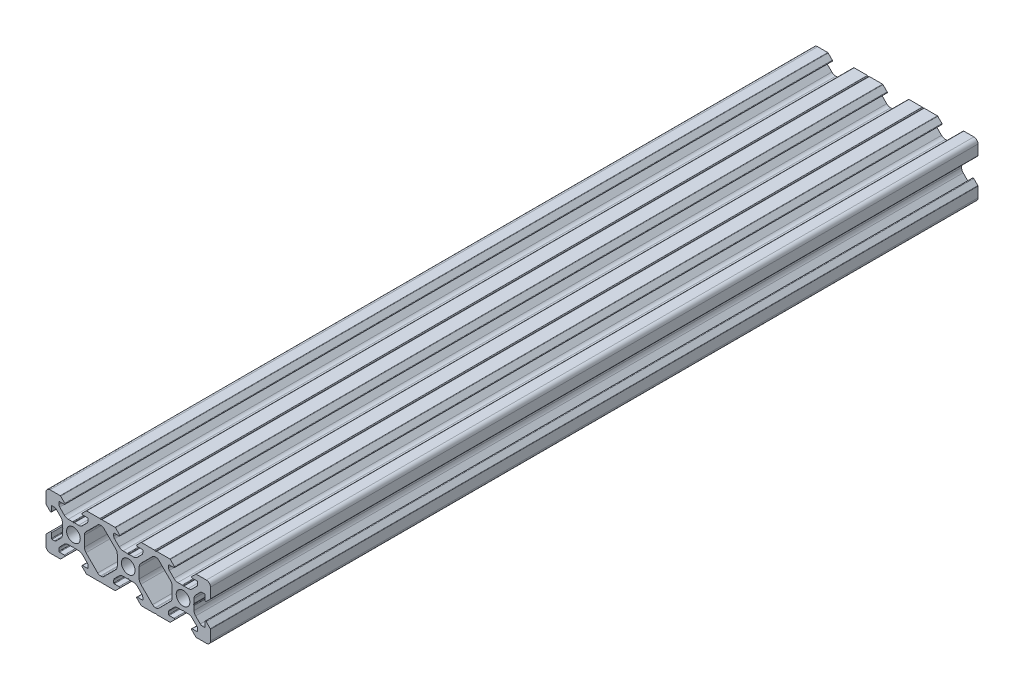
SolidWorks part; units mm, degrees
material "6061 Сплав"
ref_plane "Спереди" through (0, 0, 0) normal (0, 0, 1) x (1, 0, 0)
ref_plane "Сверху" through (0, 0, 0) normal (0, 1, 0) x (1, 0, 0)
ref_plane "Справа" through (0, 0, 0) normal (1, 0, 0) x (0, 0, -1)
sketch "Сечение" plane through (0, 0, 0) normal (0, 0, 1) x (1, 0, 0)
  line L84 (77.3691, 77.5727) -> (77.3691, 81.3703)
  line L85 (76.7833, 82.7845) -> (72.5063, 87.0614)
  line L86 (71.5164, 87.4715) -> (71.2217, 87.4715)
  line L87 (65.9548, 82.7845) -> (70.2318, 87.0614)
  line L88 (65.3691, 77.5727) -> (65.3691, 81.3703)
  line L89 (65.9548, 76.1585) -> (70.2318, 71.8815)
  line L90 (71.5164, 71.4715) -> (71.2217, 71.4715)
  line L91 (76.7833, 76.1585) -> (72.5063, 71.8815)
  line L92 (45.9548, 76.1585) -> (50.2318, 71.8815)
  line L93 (51.2217, 71.4715) -> (51.5164, 71.4715)
  line L94 (56.7833, 76.1585) -> (52.5063, 71.8815)
  line L95 (57.3691, 77.5727) -> (57.3691, 81.3703)
  line L96 (56.7833, 82.7845) -> (52.5063, 87.0614)
  line L97 (51.2217, 87.4715) -> (51.5164, 87.4715)
  line L98 (45.9548, 82.7845) -> (50.2318, 87.0614)
  line L99 (45.3691, 77.5727) -> (45.3691, 81.3703)
  line L100 (37.3691, 79.8092) -> (37.3691, 81.3703)
  line L101 (36.7833, 82.7845) -> (35.0892, 84.4786)
  line L102 (34.382, 84.7715) -> (33.5691, 84.7715)
  line L103 (33.3691, 84.5715) -> (33.3691, 82.8015)
  line L104 (31.4423, 84.1247) -> (32.9423, 82.6247)
  line L105 (31.3691, 84.3015) -> (31.3691, 87.9715)
  line L106 (36.7158, 89.3983) -> (38.2158, 87.8983)
  line L107 (41.1875, 83.4167) -> (41.3691, 83.2715)
  line L108 (41.5506, 83.4167) -> (41.3691, 83.2715)
  line L109 (43.2678, 83.4715) -> (41.7067, 83.4715)
  line L110 (46.3762, 85.7514) -> (44.682, 84.0573)
  line L111 (46.6691, 87.2715) -> (46.6691, 86.4585)
  line L112 (44.6991, 87.4715) -> (46.4691, 87.4715)
  line L113 (46.0223, 89.3983) -> (44.5223, 87.8983)
  line L114 (50.9934, 89.4715) -> (46.1991, 89.4715)
  line L115 (51.3691, 89.2715) -> (51.132, 89.4295)
  line L116 (51.3691, 89.2715) -> (51.6061, 89.4295)
  line L117 (51.7447, 89.4715) -> (56.5391, 89.4715)
  line L118 (56.7158, 89.3983) -> (58.2158, 87.8983)
  line L119 (58.0391, 87.4715) -> (56.2691, 87.4715)
  line L120 (56.0691, 87.2715) -> (56.0691, 86.4585)
  line L121 (56.3619, 85.7514) -> (58.0561, 84.0573)
  line L122 (59.4703, 83.4715) -> (61.0314, 83.4715)
  line L123 (61.1875, 83.4167) -> (61.3691, 83.2715)
  line L124 (61.5506, 83.4167) -> (61.3691, 83.2715)
  line L125 (63.2678, 83.4715) -> (61.7067, 83.4715)
  line L126 (66.3762, 85.7514) -> (64.682, 84.0573)
  line L127 (66.6691, 87.2715) -> (66.6691, 86.4585)
  line L128 (64.6991, 87.4715) -> (66.4691, 87.4715)
  line L129 (66.0223, 89.3983) -> (64.5223, 87.8983)
  line L130 (70.9934, 89.4715) -> (66.1991, 89.4715)
  line L131 (71.3691, 89.2715) -> (71.132, 89.4295)
  line L132 (71.3691, 89.2715) -> (71.6061, 89.4295)
  line L133 (71.7447, 89.4715) -> (76.5391, 89.4715)
  line L134 (76.7158, 89.3983) -> (78.2158, 87.8983)
  line L135 (78.0391, 87.4715) -> (76.2691, 87.4715)
  line L136 (76.0691, 87.2715) -> (76.0691, 86.4585)
  line L137 (76.3619, 85.7514) -> (78.0561, 84.0573)
  line L138 (79.4703, 83.4715) -> (81.0314, 83.4715)
  line L139 (81.1875, 83.4167) -> (81.3691, 83.2715)
  line L140 (81.5506, 83.4167) -> (81.3691, 83.2715)
  line L141 (84.682, 84.0573) -> (86.3762, 85.7514)
  line L142 (86.6691, 86.4585) -> (86.6691, 87.2715)
  line L143 (86.4691, 87.4715) -> (84.6991, 87.4715)
  line L144 (86.0223, 89.3983) -> (84.5223, 87.8983)
  line L145 (86.1991, 89.4715) -> (89.8691, 89.4715)
  line L146 (91.3691, 84.3015) -> (91.3691, 87.9715)
  line L147 (91.2958, 84.1247) -> (89.7958, 82.6247)
  line L148 (89.3691, 84.5715) -> (89.3691, 82.8015)
  line L149 (88.3561, 84.7715) -> (89.1691, 84.7715)
  line L150 (85.9548, 82.7845) -> (87.649, 84.4786)
  line L151 (85.3691, 79.8092) -> (85.3691, 81.3703)
  line L152 (85.3143, 79.653) -> (85.1691, 79.4715)
  line L153 (85.3143, 79.29) -> (85.1691, 79.4715)
  line L154 (85.3691, 79.1338) -> (85.3691, 77.5727)
  line L155 (85.9548, 76.1585) -> (87.649, 74.4644)
  line L156 (88.3561, 74.1715) -> (89.1691, 74.1715)
  line L157 (89.3691, 74.3715) -> (89.3691, 76.1415)
  line L158 (91.2958, 74.8183) -> (89.7958, 76.3183)
  line L159 (91.3691, 74.6415) -> (91.3691, 70.9715)
  line L160 (86.1991, 69.4715) -> (89.8691, 69.4715)
  line L161 (86.0223, 69.5447) -> (84.5223, 71.0447)
  line L162 (86.4691, 71.4715) -> (84.6991, 71.4715)
  line L163 (86.6691, 72.4845) -> (86.6691, 71.6715)
  line L164 (84.682, 74.8857) -> (86.3762, 73.1916)
  line L165 (81.7067, 75.4715) -> (83.2678, 75.4715)
  line L166 (81.5506, 75.5263) -> (81.3691, 75.6715)
  line L167 (81.1875, 75.5263) -> (81.3691, 75.6715)
  line L168 (79.4703, 75.4715) -> (81.0314, 75.4715)
  line L169 (76.3619, 73.1916) -> (78.0561, 74.8857)
  line L170 (76.0691, 71.6715) -> (76.0691, 72.4845)
  line L171 (78.0391, 71.4715) -> (76.2691, 71.4715)
  line L172 (76.7158, 69.5447) -> (78.2158, 71.0447)
  line L173 (71.7447, 69.4715) -> (76.5391, 69.4715)
  line L174 (71.3691, 69.6715) -> (71.6061, 69.5135)
  line L175 (71.3691, 69.6715) -> (71.132, 69.5135)
  line L176 (70.9934, 69.4715) -> (66.1991, 69.4715)
  line L177 (66.0223, 69.5447) -> (64.5223, 71.0447)
  line L178 (64.6991, 71.4715) -> (66.4691, 71.4715)
  line L179 (66.6691, 71.6715) -> (66.6691, 72.4845)
  line L180 (66.3762, 73.1916) -> (64.682, 74.8857)
  line L181 (63.2678, 75.4715) -> (61.7067, 75.4715)
  line L182 (61.5506, 75.5263) -> (61.3691, 75.6715)
  line L183 (61.1875, 75.5263) -> (61.3691, 75.6715)
  line L184 (59.4703, 75.4715) -> (61.0314, 75.4715)
  line L185 (56.3619, 73.1916) -> (58.0561, 74.8857)
  line L186 (56.0691, 71.6715) -> (56.0691, 72.4845)
  line L187 (58.0391, 71.4715) -> (56.2691, 71.4715)
  line L188 (56.7158, 69.5447) -> (58.2158, 71.0447)
  line L189 (51.7447, 69.4715) -> (56.5391, 69.4715)
  line L190 (51.3691, 69.6715) -> (51.6061, 69.5135)
  line L191 (51.3691, 69.6715) -> (51.132, 69.5135)
  line L192 (50.9934, 69.4715) -> (46.1991, 69.4715)
  line L193 (46.0223, 69.5447) -> (44.5223, 71.0447)
  line L194 (44.6991, 71.4715) -> (46.4691, 71.4715)
  line L195 (46.6691, 71.6715) -> (46.6691, 72.4845)
  line L196 (46.3762, 73.1916) -> (44.682, 74.8857)
  line L197 (43.2678, 75.4715) -> (41.7067, 75.4715)
  line L198 (41.5506, 75.5263) -> (41.3691, 75.6715)
  line L199 (41.1875, 75.5263) -> (41.3691, 75.6715)
  line L200 (41.0314, 75.4715) -> (39.4703, 75.4715)
  line L201 (38.0561, 74.8857) -> (36.3619, 73.1916)
  line L202 (36.0691, 72.4845) -> (36.0691, 71.6715)
  line L203 (36.2691, 71.4715) -> (38.0391, 71.4715)
  line L204 (36.7158, 69.5447) -> (38.2158, 71.0447)
  line L205 (36.5391, 69.4715) -> (32.8691, 69.4715)
  line L206 (31.3691, 74.6415) -> (31.3691, 70.9715)
  line L207 (31.4423, 74.8183) -> (32.9423, 76.3183)
  line L208 (33.3691, 74.3715) -> (33.3691, 76.1415)
  line L209 (34.382, 74.1715) -> (33.5691, 74.1715)
  line L210 (36.7833, 76.1585) -> (35.0892, 74.4644)
  line L211 (37.3691, 79.1338) -> (37.3691, 77.5727)
  line L212 (37.4238, 79.29) -> (37.5691, 79.4715)
  line L213 (37.4238, 79.653) -> (37.5691, 79.4715)
  line L214 (81.7067, 83.4715) -> (83.2678, 83.4715)
  line L215 (41.0314, 83.4715) -> (39.4703, 83.4715)
  line L216 (38.0561, 84.0573) -> (36.3619, 85.7514)
  line L217 (36.0691, 86.4585) -> (36.0691, 87.2715)
  line L218 (36.2691, 87.4715) -> (38.0391, 87.4715)
  line L219 (36.5391, 89.4715) -> (32.8691, 89.4715)
  circle A0 centre (81.3691, 79.4715) radius 2.5
  arc A1 (77.3691, 81.3703) -> (76.7833, 82.7845) centre (75.3691, 81.3703) ccw
  arc A2 (72.5063, 87.0614) -> (71.5164, 87.4715) centre (71.5164, 86.0715) ccw
  arc A3 (71.2217, 87.4715) -> (70.2318, 87.0614) centre (71.2217, 86.0715) ccw
  arc A4 (65.9548, 82.7845) -> (65.3691, 81.3703) centre (67.3691, 81.3703) ccw
  arc A5 (65.3691, 77.5727) -> (65.9548, 76.1585) centre (67.3691, 77.5727) ccw
  arc A6 (70.2318, 71.8815) -> (71.2217, 71.4715) centre (71.2217, 72.8715) ccw
  arc A7 (71.5164, 71.4715) -> (72.5063, 71.8815) centre (71.5164, 72.8715) ccw
  arc A8 (76.7833, 76.1585) -> (77.3691, 77.5727) centre (75.3691, 77.5727) ccw
  arc A9 (50.2318, 71.8815) -> (51.2217, 71.4715) centre (51.2217, 72.8715) ccw
  arc A10 (51.5164, 71.4715) -> (52.5063, 71.8815) centre (51.5164, 72.8715) ccw
  arc A11 (56.7833, 76.1585) -> (57.3691, 77.5727) centre (55.3691, 77.5727) ccw
  arc A12 (57.3691, 81.3703) -> (56.7833, 82.7845) centre (55.3691, 81.3703) ccw
  arc A13 (52.5063, 87.0614) -> (51.5164, 87.4715) centre (51.5164, 86.0715) ccw
  arc A14 (51.2217, 87.4715) -> (50.2318, 87.0614) centre (51.2217, 86.0715) ccw
  arc A15 (45.9548, 82.7845) -> (45.3691, 81.3703) centre (47.3691, 81.3703) ccw
  arc A16 (45.3691, 77.5727) -> (45.9548, 76.1585) centre (47.3691, 77.5727) ccw
  arc A17 (37.3691, 79.8092) -> (37.4238, 79.653) centre (37.6191, 79.8092) ccw
  arc A18 (37.3691, 81.3703) -> (36.7833, 82.7845) centre (35.3691, 81.3703) ccw
  arc A19 (35.0892, 84.4786) -> (34.382, 84.7715) centre (34.382, 83.7715) ccw
  arc A20 (33.5691, 84.7715) -> (33.3691, 84.5715) centre (33.5691, 84.5715) ccw
  arc A21 (32.9423, 82.6247) -> (33.3691, 82.8015) centre (33.1191, 82.8015) ccw
  arc A22 (31.3691, 84.3015) -> (31.4423, 84.1247) centre (31.6191, 84.3015) ccw
  arc A23 (32.8691, 89.4715) -> (31.3691, 87.9715) centre (32.8691, 87.9715) ccw
  arc A24 (36.7158, 89.3983) -> (36.5391, 89.4715) centre (36.5391, 89.2215) ccw
  arc A25 (38.0391, 87.4715) -> (38.2158, 87.8983) centre (38.0391, 87.7215) ccw
  arc A26 (36.2691, 87.4715) -> (36.0691, 87.2715) centre (36.2691, 87.2715) ccw
  arc A27 (36.0691, 86.4585) -> (36.3619, 85.7514) centre (37.0691, 86.4585) ccw
  arc A28 (38.0561, 84.0573) -> (39.4703, 83.4715) centre (39.4703, 85.4715) ccw
  arc A29 (41.1875, 83.4167) -> (41.0314, 83.4715) centre (41.0314, 83.2215) ccw
  arc A30 (41.7067, 83.4715) -> (41.5506, 83.4167) centre (41.7067, 83.2215) ccw
  arc A31 (43.2678, 83.4715) -> (44.682, 84.0573) centre (43.2678, 85.4715) ccw
  arc A32 (46.3762, 85.7514) -> (46.6691, 86.4585) centre (45.6691, 86.4585) ccw
  arc A33 (46.6691, 87.2715) -> (46.4691, 87.4715) centre (46.4691, 87.2715) ccw
  arc A34 (44.5223, 87.8983) -> (44.6991, 87.4715) centre (44.6991, 87.7215) ccw
  arc A35 (46.1991, 89.4715) -> (46.0223, 89.3983) centre (46.1991, 89.2215) ccw
  arc A36 (51.132, 89.4295) -> (50.9934, 89.4715) centre (50.9934, 89.2215) ccw
  arc A37 (51.7447, 89.4715) -> (51.6061, 89.4295) centre (51.7447, 89.2215) ccw
  arc A38 (56.7158, 89.3983) -> (56.5391, 89.4715) centre (56.5391, 89.2215) ccw
  arc A39 (58.0391, 87.4715) -> (58.2158, 87.8983) centre (58.0391, 87.7215) ccw
  arc A40 (56.2691, 87.4715) -> (56.0691, 87.2715) centre (56.2691, 87.2715) ccw
  arc A41 (56.0691, 86.4585) -> (56.3619, 85.7514) centre (57.0691, 86.4585) ccw
  arc A42 (58.0561, 84.0573) -> (59.4703, 83.4715) centre (59.4703, 85.4715) ccw
  arc A43 (61.1875, 83.4167) -> (61.0314, 83.4715) centre (61.0314, 83.2215) ccw
  arc A44 (61.7067, 83.4715) -> (61.5506, 83.4167) centre (61.7067, 83.2215) ccw
  arc A45 (63.2678, 83.4715) -> (64.682, 84.0573) centre (63.2678, 85.4715) ccw
  arc A46 (66.3762, 85.7514) -> (66.6691, 86.4585) centre (65.6691, 86.4585) ccw
  arc A47 (66.6691, 87.2715) -> (66.4691, 87.4715) centre (66.4691, 87.2715) ccw
  arc A48 (64.5223, 87.8983) -> (64.6991, 87.4715) centre (64.6991, 87.7215) ccw
  arc A49 (66.1991, 89.4715) -> (66.0223, 89.3983) centre (66.1991, 89.2215) ccw
  arc A50 (71.132, 89.4295) -> (70.9934, 89.4715) centre (70.9934, 89.2215) ccw
  arc A51 (71.7447, 89.4715) -> (71.6061, 89.4295) centre (71.7447, 89.2215) ccw
  arc A52 (76.7158, 89.3983) -> (76.5391, 89.4715) centre (76.5391, 89.2215) ccw
  arc A53 (78.0391, 87.4715) -> (78.2158, 87.8983) centre (78.0391, 87.7215) ccw
  arc A54 (76.2691, 87.4715) -> (76.0691, 87.2715) centre (76.2691, 87.2715) ccw
  arc A55 (76.0691, 86.4585) -> (76.3619, 85.7514) centre (77.0691, 86.4585) ccw
  arc A56 (78.0561, 84.0573) -> (79.4703, 83.4715) centre (79.4703, 85.4715) ccw
  arc A57 (81.1875, 83.4167) -> (81.0314, 83.4715) centre (81.0314, 83.2215) ccw
  arc A58 (81.7067, 83.4715) -> (81.5506, 83.4167) centre (81.7067, 83.2215) ccw
  arc A59 (83.2678, 83.4715) -> (84.682, 84.0573) centre (83.2678, 85.4715) ccw
  arc A60 (86.3762, 85.7514) -> (86.6691, 86.4585) centre (85.6691, 86.4585) ccw
  arc A61 (86.6691, 87.2715) -> (86.4691, 87.4715) centre (86.4691, 87.2715) ccw
  arc A62 (84.5223, 87.8983) -> (84.6991, 87.4715) centre (84.6991, 87.7215) ccw
  arc A63 (86.1991, 89.4715) -> (86.0223, 89.3983) centre (86.1991, 89.2215) ccw
  arc A64 (91.3691, 87.9715) -> (89.8691, 89.4715) centre (89.8691, 87.9715) ccw
  arc A65 (91.2958, 84.1247) -> (91.3691, 84.3015) centre (91.1191, 84.3015) ccw
  arc A66 (89.3691, 82.8015) -> (89.7958, 82.6247) centre (89.6191, 82.8015) ccw
  arc A67 (89.3691, 84.5715) -> (89.1691, 84.7715) centre (89.1691, 84.5715) ccw
  arc A68 (88.3561, 84.7715) -> (87.649, 84.4786) centre (88.3561, 83.7715) ccw
  arc A69 (85.9548, 82.7845) -> (85.3691, 81.3703) centre (87.3691, 81.3703) ccw
  arc A70 (85.3143, 79.653) -> (85.3691, 79.8092) centre (85.1191, 79.8092) ccw
  arc A71 (85.3691, 79.1338) -> (85.3143, 79.29) centre (85.1191, 79.1338) ccw
  arc A72 (85.3691, 77.5727) -> (85.9548, 76.1585) centre (87.3691, 77.5727) ccw
  arc A73 (87.649, 74.4644) -> (88.3561, 74.1715) centre (88.3561, 75.1715) ccw
  arc A74 (89.1691, 74.1715) -> (89.3691, 74.3715) centre (89.1691, 74.3715) ccw
  arc A75 (89.7958, 76.3183) -> (89.3691, 76.1415) centre (89.6191, 76.1415) ccw
  arc A76 (91.3691, 74.6415) -> (91.2958, 74.8183) centre (91.1191, 74.6415) ccw
  arc A77 (89.8691, 69.4715) -> (91.3691, 70.9715) centre (89.8691, 70.9715) ccw
  arc A78 (86.0223, 69.5447) -> (86.1991, 69.4715) centre (86.1991, 69.7215) ccw
  arc A79 (84.6991, 71.4715) -> (84.5223, 71.0447) centre (84.6991, 71.2215) ccw
  arc A80 (86.4691, 71.4715) -> (86.6691, 71.6715) centre (86.4691, 71.6715) ccw
  arc A81 (86.6691, 72.4845) -> (86.3762, 73.1916) centre (85.6691, 72.4845) ccw
  arc A82 (84.682, 74.8857) -> (83.2678, 75.4715) centre (83.2678, 73.4715) ccw
  arc A83 (81.5506, 75.5263) -> (81.7067, 75.4715) centre (81.7067, 75.7215) ccw
  arc A84 (81.0314, 75.4715) -> (81.1875, 75.5263) centre (81.0314, 75.7215) ccw
  arc A85 (79.4703, 75.4715) -> (78.0561, 74.8857) centre (79.4703, 73.4715) ccw
  arc A86 (76.3619, 73.1916) -> (76.0691, 72.4845) centre (77.0691, 72.4845) ccw
  arc A87 (76.0691, 71.6715) -> (76.2691, 71.4715) centre (76.2691, 71.6715) ccw
  arc A88 (78.2158, 71.0447) -> (78.0391, 71.4715) centre (78.0391, 71.2215) ccw
  arc A89 (76.5391, 69.4715) -> (76.7158, 69.5447) centre (76.5391, 69.7215) ccw
  arc A90 (71.6061, 69.5135) -> (71.7447, 69.4715) centre (71.7447, 69.7215) ccw
  arc A91 (70.9934, 69.4715) -> (71.132, 69.5135) centre (70.9934, 69.7215) ccw
  arc A92 (66.0223, 69.5447) -> (66.1991, 69.4715) centre (66.1991, 69.7215) ccw
  arc A93 (64.6991, 71.4715) -> (64.5223, 71.0447) centre (64.6991, 71.2215) ccw
  arc A94 (66.4691, 71.4715) -> (66.6691, 71.6715) centre (66.4691, 71.6715) ccw
  arc A95 (66.6691, 72.4845) -> (66.3762, 73.1916) centre (65.6691, 72.4845) ccw
  arc A96 (64.682, 74.8857) -> (63.2678, 75.4715) centre (63.2678, 73.4715) ccw
  arc A97 (61.5506, 75.5263) -> (61.7067, 75.4715) centre (61.7067, 75.7215) ccw
  arc A98 (61.0314, 75.4715) -> (61.1875, 75.5263) centre (61.0314, 75.7215) ccw
  arc A99 (59.4703, 75.4715) -> (58.0561, 74.8857) centre (59.4703, 73.4715) ccw
  arc A100 (56.3619, 73.1916) -> (56.0691, 72.4845) centre (57.0691, 72.4845) ccw
  arc A101 (56.0691, 71.6715) -> (56.2691, 71.4715) centre (56.2691, 71.6715) ccw
  arc A102 (58.2158, 71.0447) -> (58.0391, 71.4715) centre (58.0391, 71.2215) ccw
  arc A103 (56.5391, 69.4715) -> (56.7158, 69.5447) centre (56.5391, 69.7215) ccw
  arc A104 (51.6061, 69.5135) -> (51.7447, 69.4715) centre (51.7447, 69.7215) ccw
  arc A105 (50.9934, 69.4715) -> (51.132, 69.5135) centre (50.9934, 69.7215) ccw
  arc A106 (46.0223, 69.5447) -> (46.1991, 69.4715) centre (46.1991, 69.7215) ccw
  arc A107 (44.6991, 71.4715) -> (44.5223, 71.0447) centre (44.6991, 71.2215) ccw
  arc A108 (46.4691, 71.4715) -> (46.6691, 71.6715) centre (46.4691, 71.6715) ccw
  arc A109 (46.6691, 72.4845) -> (46.3762, 73.1916) centre (45.6691, 72.4845) ccw
  arc A110 (44.682, 74.8857) -> (43.2678, 75.4715) centre (43.2678, 73.4715) ccw
  arc A111 (41.5506, 75.5263) -> (41.7067, 75.4715) centre (41.7067, 75.7215) ccw
  arc A112 (41.0314, 75.4715) -> (41.1875, 75.5263) centre (41.0314, 75.7215) ccw
  arc A113 (39.4703, 75.4715) -> (38.0561, 74.8857) centre (39.4703, 73.4715) ccw
  arc A114 (36.3619, 73.1916) -> (36.0691, 72.4845) centre (37.0691, 72.4845) ccw
  arc A115 (36.0691, 71.6715) -> (36.2691, 71.4715) centre (36.2691, 71.6715) ccw
  arc A116 (38.2158, 71.0447) -> (38.0391, 71.4715) centre (38.0391, 71.2215) ccw
  arc A117 (36.5391, 69.4715) -> (36.7158, 69.5447) centre (36.5391, 69.7215) ccw
  arc A118 (31.3691, 70.9715) -> (32.8691, 69.4715) centre (32.8691, 70.9715) ccw
  arc A119 (31.4423, 74.8183) -> (31.3691, 74.6415) centre (31.6191, 74.6415) ccw
  arc A120 (33.3691, 76.1415) -> (32.9423, 76.3183) centre (33.1191, 76.1415) ccw
  arc A121 (33.3691, 74.3715) -> (33.5691, 74.1715) centre (33.5691, 74.3715) ccw
  arc A122 (34.382, 74.1715) -> (35.0892, 74.4644) centre (34.382, 75.1715) ccw
  arc A123 (36.7833, 76.1585) -> (37.3691, 77.5727) centre (35.3691, 77.5727) ccw
  arc A124 (37.4238, 79.29) -> (37.3691, 79.1338) centre (37.6191, 79.1338) ccw
  circle A125 centre (61.3691, 79.4715) radius 2.5
  circle A126 centre (41.3691, 79.4715) radius 2.5
  point P518 (31.3691, 84.1979)
  point P519 (31.3691, 74.745)
extrude "Длина" add sketch "Сечение" along normal blind 280
